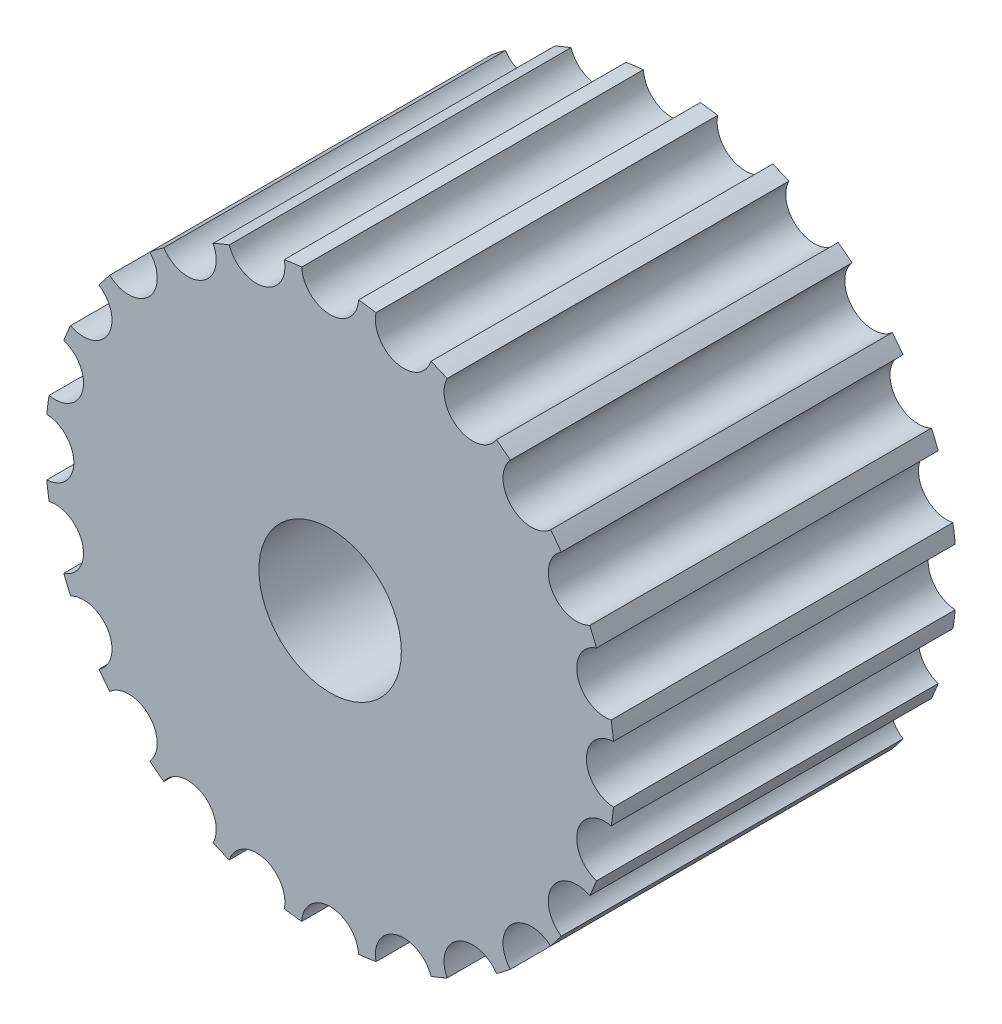
SolidWorks part; units mm, degrees
ref_plane "前视基准面" through (0, 0, 0) normal (0, 0, 1) x (1, 0, 0)
ref_plane "上视基准面" through (0, 0, 0) normal (0, 1, 0) x (1, 0, 0)
ref_plane "右视基准面" through (0, 0, 0) normal (1, 0, 0) x (0, 0, -1)
sketch "Sketch1" plane through (0, 0, 0) normal (0, 0, 1) x (1, 0, 0)
  circle A0 centre (0, 0) radius 10
  dimension "D1" = 20
extrude "Boss-Extrude1" add sketch "Sketch1" along normal blind 12
sketch "Sketch2" plane through (0, 0, 12) normal (0, 0, 1) x (1, 0, 0)
  circle A0 centre (0, 10) radius 1
  circle A1 centre (0, 0) radius 10 construction
  circle A2 centre (2.5882, 9.6593) radius 1
  circle A3 centre (5, 8.6603) radius 1
  circle A4 centre (7.0711, 7.0711) radius 1
  circle A5 centre (8.6603, 5) radius 1
  circle A6 centre (9.6593, 2.5882) radius 1
  circle A7 centre (10, 0) radius 1
  circle A8 centre (9.6593, -2.5882) radius 1
  circle A9 centre (8.6603, -5) radius 1
  circle A10 centre (7.0711, -7.0711) radius 1
  circle A11 centre (5, -8.6603) radius 1
  circle A12 centre (2.5882, -9.6593) radius 1
  circle A13 centre (0, -10) radius 1
  circle A14 centre (-2.5882, -9.6593) radius 1
  circle A15 centre (-5, -8.6603) radius 1
  circle A16 centre (-7.0711, -7.0711) radius 1
  circle A17 centre (-8.6603, -5) radius 1
  circle A18 centre (-9.6593, -2.5882) radius 1
  circle A19 centre (-10, 0) radius 1
  circle A20 centre (-9.6593, 2.5882) radius 1
  circle A21 centre (-8.6603, 5) radius 1
  circle A22 centre (-7.0711, 7.0711) radius 1
  circle A23 centre (-5, 8.6603) radius 1
  circle A24 centre (-2.5882, 9.6593) radius 1
  dimension "D1" = 24
extrude "Cut-Extrude1" cut sketch "Sketch2" against normal through all both and the other way through all
sketch "Sketch3" plane through (0, 0, 12) normal (0, 0, 1) x (1, 0, 0)
  circle A0 centre (0, 0) radius 2.5
extrude "Cut-Extrude2" cut sketch "Sketch3" against normal through all
